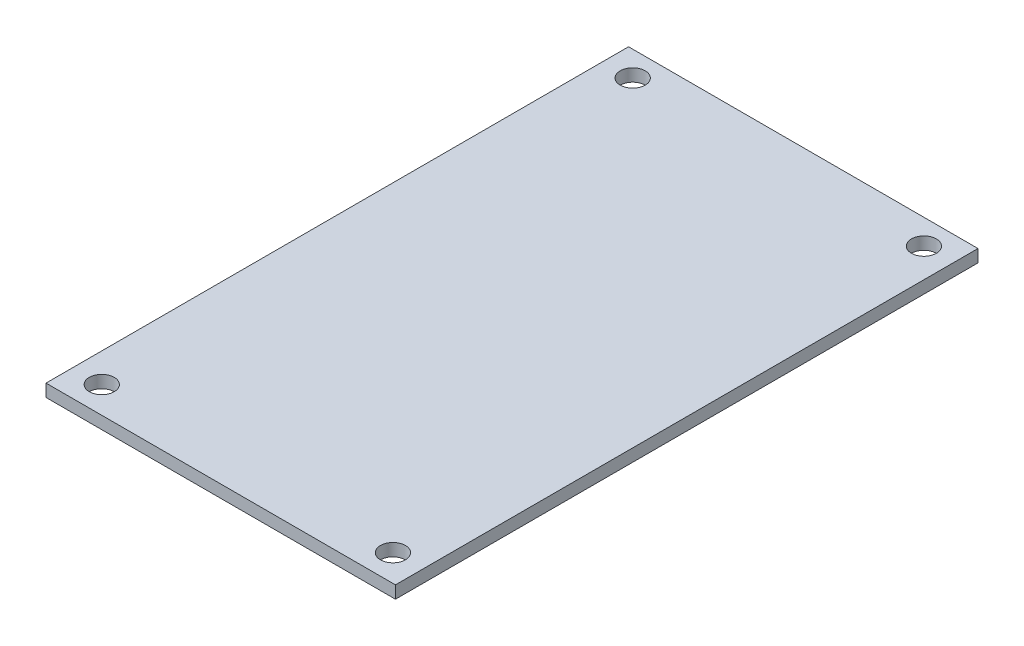
SolidWorks part; units mm, degrees
material "Custom Plastic"
ref_plane "Front Plane" through (0, 0, 0) normal (0, 0, 1) x (1, 0, 0)
ref_plane "Top Plane" through (0, 0, 0) normal (0, 1, 0) x (1, 0, 0)
ref_plane "Right Plane" through (0, 0, 0) normal (1, 0, 0) x (0, 0, -1)
sketch "Sketch1" plane through (0, 0, 0) normal (0, 1, 0) x (1, 0, 0)
  line L0 (3.5, 70.1354) -> (3.5, 50070.1354) construction
  line L1 (0, 0) -> (42, 0)
  line L2 (0, 0) -> (0, 70.0156)
  line L3 (0, 70.0156) -> (42, 70.0156)
  line L4 (42, 0) -> (42, 70.0156)
  line L5 (52.5654, 67.0156) -> (50052.5654, 67.0156) construction
  line L6 (38.5, 70.1354) -> (38.5, 50070.1354) construction
  line L7 (0, 3.2) -> (-50000, 3.2) construction
  circle A0 centre (3.5, 67.0156) radius 1.5
  circle A1 centre (38.5, 67.0156) radius 1.5
  circle A2 centre (3.5, 3.2) radius 1.5
  circle A3 centre (38.5, 3.2) radius 1.5
  dimension "D2" = 3
  dimension "D3" = 3
  dimension "D4" = 3.5
  dimension "D1" = 3.5
  dimension "D5" = 42
  dimension "D6" = 3.2
extrude "Boss-Extrude1" add sketch "Sketch1" along normal blind 1.5
